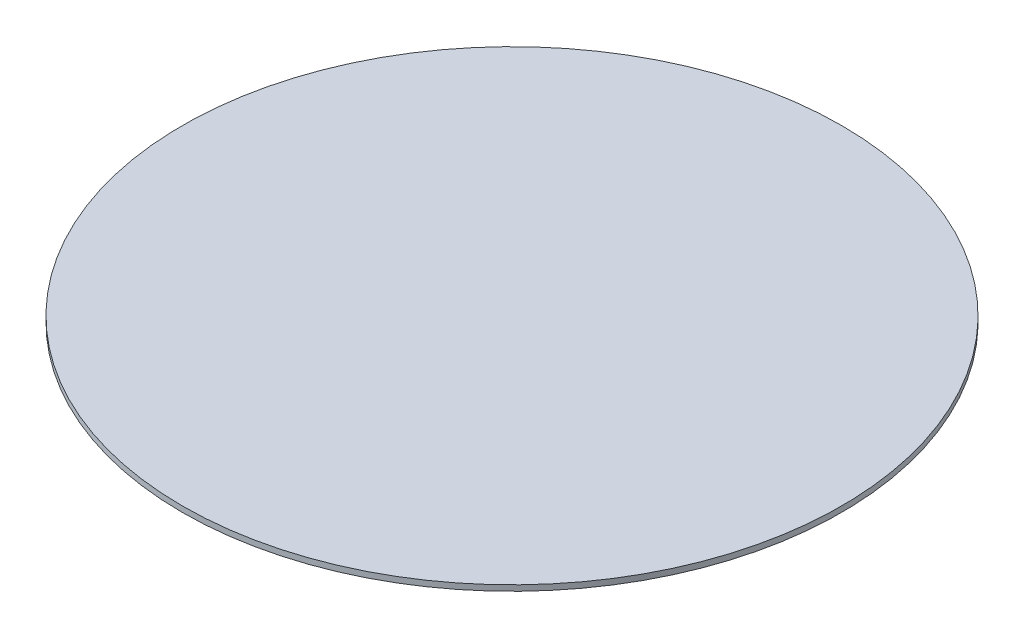
SolidWorks part; units mm, degrees
ref_plane "Front Plane" through (0, 0, 0) normal (0, 0, 1) x (1, 0, 0)
ref_plane "Top Plane" through (0, 0, 0) normal (0, 1, 0) x (1, 0, 0)
ref_plane "Right Plane" through (0, 0, 0) normal (1, 0, 0) x (0, 0, -1)
sketch "Sketch1" plane through (0, 0, 0) normal (0, 1, 0) x (1, 0, 0)
  circle A0 centre (0, 0) radius 175
  dimension "D1" = 350
extrude "Boss-Extrude1" add sketch "Sketch1" along normal blind 3
